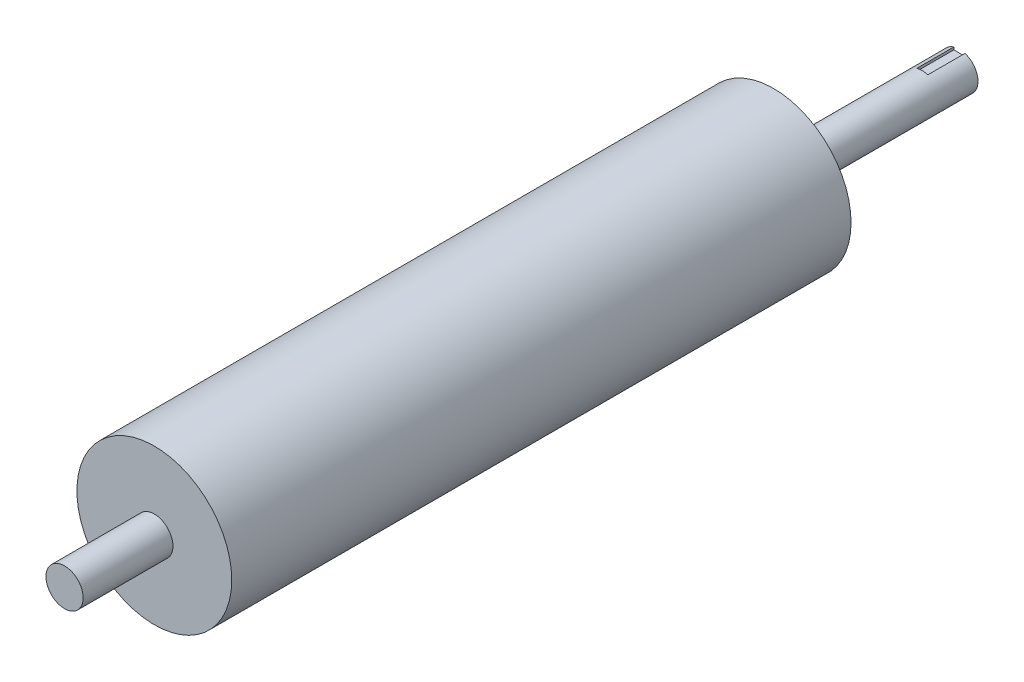
SolidWorks part; units mm, degrees
material "AISI 1020 Steel, Cold Rolled"
ref_plane "Front Plane" through (0, 0, 0) normal (0, 0, 1) x (1, 0, 0)
ref_plane "Top Plane" through (0, 0, 0) normal (0, 1, 0) x (1, 0, 0)
ref_plane "Right Plane" through (0, 0, 0) normal (1, 0, 0) x (0, 0, -1)
sketch "Sketch2" plane through (0, 0, 0) normal (0, 0, 1) x (1, 0, 0)
  line L0 (0, 125) -> (0, 209.7943) construction
  line L1 (-125, 0) -> (-247.6393, 0) construction
  line L2 (-88.3883, -88.3883) -> (-164.03, -164.03) construction
  circle A0 centre (0, 0) radius 125
  point P6 (0, 167.3971)
  dimension "D1" = 250
extrude "Boss-Extrude1" add sketch "Sketch2" along normal blind 1000
sketch "Sketch7" plane through (0, 0, 1000) normal (0, 0, 1) x (1, 0, 0)
  circle A0 centre (0, 0) radius 30
  dimension "D1" = 60
extrude "Boss-Extrude3" add sketch "Sketch7" along normal blind 145
sketch "Sketch8" plane through (0, 0, 0) normal (0, 0, -1) x (-1, 0, 0)
  circle A0 centre (0, 0) radius 30
  dimension "D1" = 60
extrude "Boss-Extrude4" add sketch "Sketch8" along normal blind 300
sketch "Sketch9" plane through (0, 0, -300) normal (0, 0, -1) x (-1, 0, 0)
  line L1 (-9, 24.5) -> (9, 24.5)
  line L2 (-9, 24.5) -> (-9, 35.5)
  line L3 (-9, 35.5) -> (9, 35.5)
  line L4 (9, 24.5) -> (9, 35.5)
  line L5 (-9, 24.5) -> (9, 35.5) construction
  line L6 (-9, 35.5) -> (9, 24.5) construction
  circle A0 centre (0, 0) radius 30 construction
  circle A1 centre (0, 0) radius 30 construction
  point P0 (0, 30)
  dimension "D1" = 11
  dimension "D2" = 18
extrude "Cut-Extrude1" cut sketch "Sketch9" against normal blind 60 contours L3 L4 L1 L2
